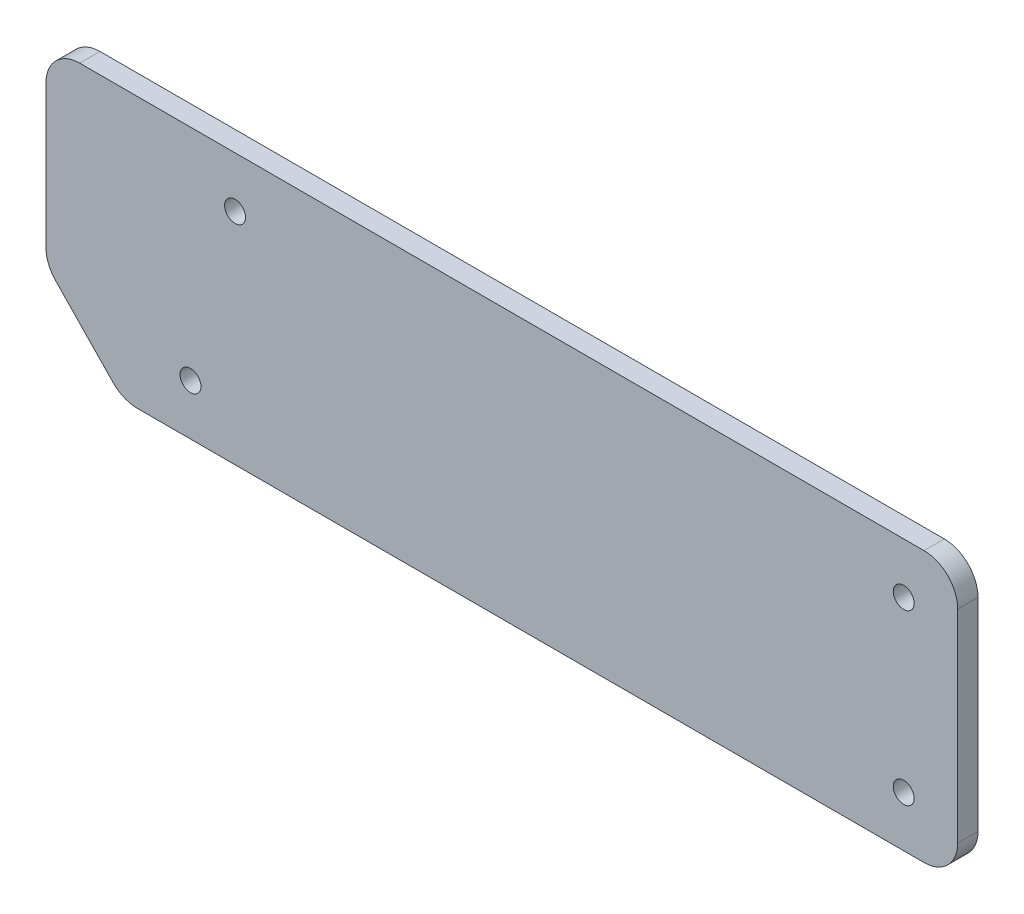
SolidWorks part; units mm, degrees
ref_plane "Front Plane" through (0, 0, 0) normal (0, 0, 1) x (1, 0, 0)
ref_plane "Top Plane" through (0, 0, 0) normal (0, 1, 0) x (1, 0, 0)
ref_plane "Right Plane" through (0, 0, 0) normal (1, 0, 0) x (0, 0, -1)
sketch "Sketch1" plane through (0, 0, 0) normal (0, 0, 1) x (1, 0, 0)
  line L1 (-135, -40) -> (135, -40)
  line L2 (-135, -40) -> (-135, 40)
  line L3 (-135, 40) -> (135, 40)
  line L4 (135, -40) -> (135, 40)
  line L5 (-135, -40) -> (135, 40) construction
  line L6 (-135, 40) -> (135, -40) construction
  point P1 (0, 0)
  dimension "D1" = 270
  dimension "D2" = 80
extrude "Boss-Extrude1" add sketch "Sketch1" along normal blind 6
sketch "Sketch2" plane through (0, 0, 6) normal (0, 0, 1) x (1, 0, 0)
  line L0 (-222.487, 25) -> (221.9728, 25) construction
  line L1 (135, 40) -> (-135, 40) construction
  line L2 (-135, 40) -> (-135, -40) construction
  circle A0 centre (-115, 25) radius 1.5 construction
  circle A1 centre (-79, 25) radius 3.1
  circle A2 centre (119, 25) radius 3.1
  circle A3 centre (119, -25) radius 3.1
  circle A4 centre (-92.21, -25) radius 3.1
  dimension "D5" = 3
  dimension "D6" = 211.21
  dimension "D8" = 6.2
  dimension "D1" = 15
  dimension "D2" = 20
  dimension "D3" = 36
  dimension "D4" = 198
  dimension "D7" = 50
extrude "Cut-Extrude1" cut sketch "Sketch2" against normal through all
fillet "Fillet1" radius 10 4 edges at (135, -40, 3) (-135, -40, 3) (135, 40, 3) (-135, 40, 3)
sketch "Sketch3" plane through (0, 0, 6) normal (0, 0, 1) x (1, 0, 0)
  line L0 (-92.21, -25) -> (-92.21, -76.1827) construction
  line L1 (-112.21, -40) -> (-154.2063, 3.4732)
  line L2 (-125, -40) -> (125, -40) construction
  line L3 (-154.2063, 3.4732) -> (-156.169, -56.5554)
  line L4 (-156.169, -56.5554) -> (-112.21, -57.9927)
  line L5 (-112.21, -57.9927) -> (-112.21, -40)
  dimension "D1" = 20
  dimension "D2" = 134.01
extrude "Cut-Extrude2" cut sketch "Sketch3" against normal blind 10
fillet "Fillet2" radius 10 2 edges at (-112.21, -40, 3) (-135, -16.4085, 3)
